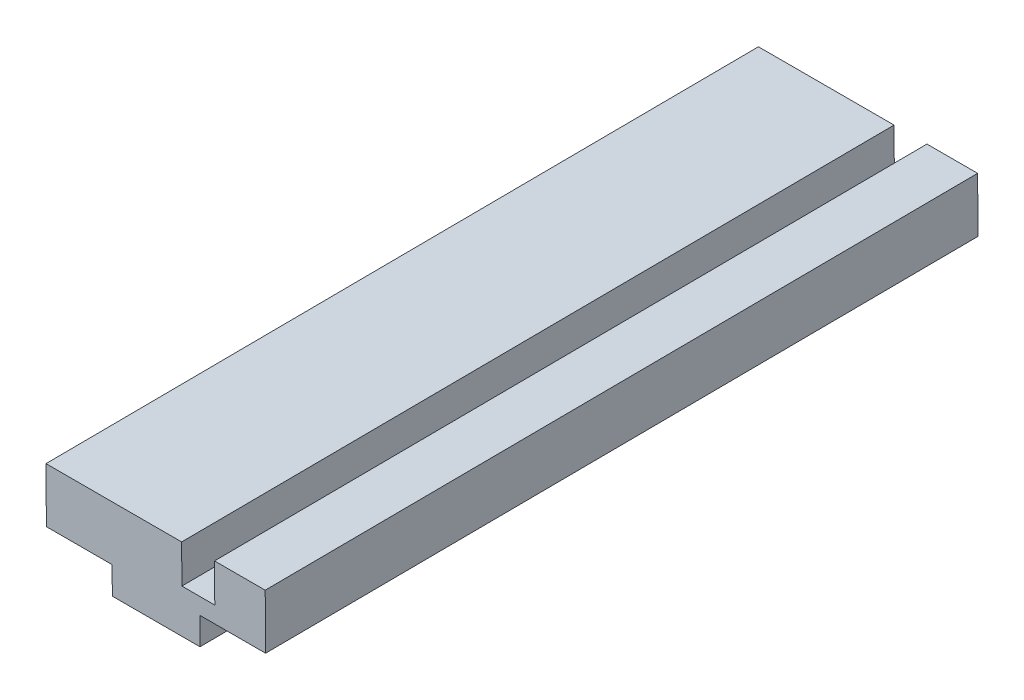
SolidWorks part; units mm, degrees
ref_plane "前视基准面" through (0, 0, 0) normal (0, 0, 1) x (1, 0, 0)
ref_plane "上视基准面" through (0, 0, 0) normal (0, 1, 0) x (1, 0, 0)
ref_plane "右视基准面" through (0, 0, 0) normal (1, 0, 0) x (0, 0, -1)
sketch "草图1" plane through (0, 0.0704, -10.4308) normal (0, -0.0068, 1) x (1, 0, 0)
  line L0 (-0.5, 9.7351) -> (-0.5, 24.7351) construction
  line L1 (4.2499, 22.7351) -> (4.2499, 17.7351)
  line L2 (4.2499, 17.7351) -> (10.2499, 17.7351)
  line L3 (10.2499, 17.7351) -> (10.2499, 22.7351)
  line L12 (7.5, 9.7351) -> (7.5, 14.7351)
  line L13 (7.5, 14.7351) -> (19.5, 14.7351)
  line L14 (19.5, 14.7351) -> (19.5, 24.7351)
  line L15 (19.5, 24.7351) -> (10.2499, 24.7351)
  line L16 (10.2499, 24.7351) -> (10.2499, 22.7351)
  line L17 (10.2499, 22.7351) -> (4.2499, 22.7351)
  line L18 (4.2499, 22.7351) -> (4.2499, 24.7351)
  line L19 (4.2499, 24.7351) -> (-20.5, 24.7351)
  line L20 (-20.5, 24.7351) -> (-20.5, 14.7351)
  line L21 (-20.5, 14.7351) -> (-8.5, 14.7351)
  line L22 (-8.5, 14.7351) -> (-8.5, 9.7351)
  line L23 (-8.5, 9.7351) -> (7.5, 9.7351)
  line L24 (7.5, 9.7351) -> (7.5, 14.7351)
  line L25 (7.5, 14.7351) -> (19.5, 14.7351)
  line L26 (19.5, 14.7351) -> (19.5, 24.7351)
  line L27 (19.5, 24.7351) -> (10.2499, 24.7351)
  line L28 (10.2499, 24.7351) -> (10.2499, 22.7351)
  line L29 (10.2499, 22.7351) -> (4.2499, 22.7351)
  line L30 (4.2499, 22.7351) -> (4.2499, 24.7351)
  line L31 (4.2499, 24.7351) -> (-20.5, 24.7351)
  line L32 (-20.5, 24.7351) -> (-20.5, 14.7351)
  line L33 (-20.5, 14.7351) -> (-8.5, 14.7351)
  line L34 (-8.5, 14.7351) -> (-8.5, 9.7351)
  line L35 (-8.5, 9.7351) -> (7.5, 9.7351)
  line M17 (7.5, 14.7351) -> (7.5, 9.7351)
  line M18 (7.5, 9.7351) -> (-8.5, 9.7351)
  line M19 (-8.5, 9.7351) -> (-8.5, 14.7351)
  line M20 (-8.5, 14.7351) -> (-20.5, 14.7351)
  line M21 (-20.5, 14.7351) -> (-20.5, 24.7351)
  line M22 (-20.5, 24.7351) -> (4.2499, 24.7351)
  line M23 (4.2499, 24.7351) -> (4.2499, 22.7351)
  line M25 (10.2499, 22.7351) -> (10.2499, 24.7351)
  line M26 (10.2499, 24.7351) -> (19.5, 24.7351)
  line M27 (19.5, 24.7351) -> (19.5, 14.7351)
  line M28 (19.5, 14.7351) -> (7.5, 14.7351)
  dimension "D2" = 5
  dimension "D1" = 0
extrude "凸台-拉伸1" add sketch "草图1" against normal blind 130 contours L35 L0 M22 M21 M20 M19 | L0 L3 L2 L1 L31 M18 M17 M28 M27 M26 M25 M23
